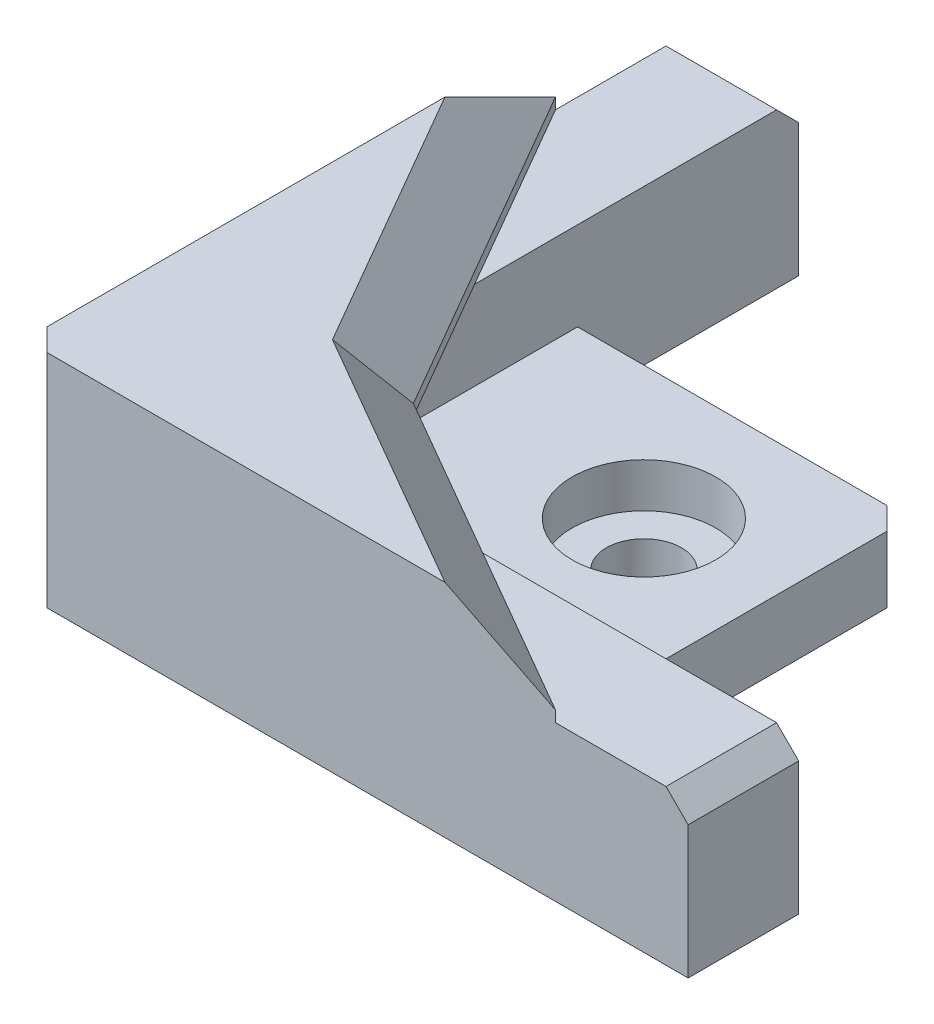
SolidWorks part; units mm, degrees
material "ABS"
ref_plane "Alzado" through (0, 0, 0) normal (0, 0, 1) x (1, 0, 0)
ref_plane "Planta" through (0, 0, 0) normal (0, 1, 0) x (1, 0, 0)
ref_plane "Vista lateral" through (0, 0, 0) normal (1, 0, 0) x (0, 0, -1)
sketch "Sketch1" plane through (0, 0, 0) normal (0, 1, 0) x (1, 0, 0)
  line L0 (0, 15) -> (0, 25)
  line L1 (0, 25) -> (-5, 25)
  line L2 (-5, 25) -> (-5, -5)
  line L3 (-5, -5) -> (25, -5)
  line L4 (25, -5) -> (25, 0)
  line L5 (25, 0) -> (15, 0)
  line L6 (0, 15) -> (15, 15)
  line L7 (15, 15) -> (15, 0)
  dimension "D1" = 20
  dimension "D2" = 30
  dimension "D3" = 5
  dimension "D4" = 5
extrude "Boss-Extrude1" add sketch "Sketch1" along normal blind 3
sketch "Sketch2" plane through (0, 3, 0) normal (0, 1, 0) x (1, 0, 0)
  line L0 (-5, 25) -> (0, 25)
  line L1 (0, 25) -> (0, 0)
  line L2 (0, 0) -> (25, 0)
  line L3 (25, 0) -> (25, -5)
  line L4 (25, -5) -> (-5, -5)
  line L5 (-5, -5) -> (-5, 25)
extrude "Boss-Extrude2" add sketch "Sketch2" along normal blind 4
sketch "Sketch3" plane through (0, 3, 0) normal (0, 1, 0) x (1, 0, 0)
  line L0 (15, 15) -> (0, 15) construction
  line L1 (15, 0) -> (15, 15) construction
  circle A0 centre (9, 9) radius 1.5
  point P0 (9, 9)
  dimension "D3" = 3
  dimension "D1" = 6
  dimension "D2" = 6
hole_wizard "Refrentado para tornillo con cabeza plana de M31" positions "Sketch3" profile "Sketch4" counterbore size "M3" standard "ISO"
sketch "Sketch4" plane through (9, 3, -9) normal (1, 0, 0) x (0, 0, 1)
  line L0 (0, 0) -> (0, 41.0215)
  line L1 (0, 41.0215) -> (1.7, 40)
  line L2 (1.7, 40) -> (1.7, 2)
  line L3 (1.7, 2) -> (3.25, 2)
  line L4 (3.25, 2) -> (3.25, 0)
  line L5 (3.25, 0) -> (0, 0)
  line L10 (0, 41.0215) -> (-1.7, 40) construction
  line L11 (0, -6.35) -> (0, 107.95) construction
  dimension "Diámetro de taladro" = 3.4
  dimension "Profundidad de taladro" = 40
  dimension "Diámetro de refrentado" = 6.5
  dimension "Profundidad de refrentado" = 2
  dimension "Ángulo de perforador" = 118
sketch "Sketch5" plane through (0, 0, 0) normal (0, -1, 0) x (1, 0, 0)
  circle A0 centre (9, -9) radius 3
  circle A1 centre (9, -9) radius 1.7
  dimension "D1" = 6
extrude "Boss-Extrude3" add sketch "Sketch5" along normal blind 2.5
sketch "Sketch6" plane through (0, 7, 0) normal (0, 1, 0) x (1, 0, 0)
  line L0 (-5, -5) -> (-5, 19)
  line L1 (-5, 25) -> (-5, -5) construction
  line L2 (-5, 19) -> (3.7882, 3.7882)
  line L3 (3.7882, 3.7882) -> (19, -5)
  line L4 (-5, -5) -> (25, -5) construction
  line L5 (19, -5) -> (-5, -5)
  line L6 (0, 0) -> (-35355.3391, -35355.3391) construction
  dimension "D1" = 24
extrude "Boss-Extrude4" add sketch "Sketch6" along normal blind 3
chamfer "Chamfer1" distance 2.5 angle 45 2 edges at (11.3941, 10, 0.6059) (-0.6059, 10, -11.3941)
chamfer "Chamfer2" distance 1 angle 45 4 edges at (-5, 5, 5) (15, 1.5, -15) (-2.5, 7, -25) (25, 7, 2.5)
fillet "Fillet2" radius 1 1 edges at (9, 0, -6)
